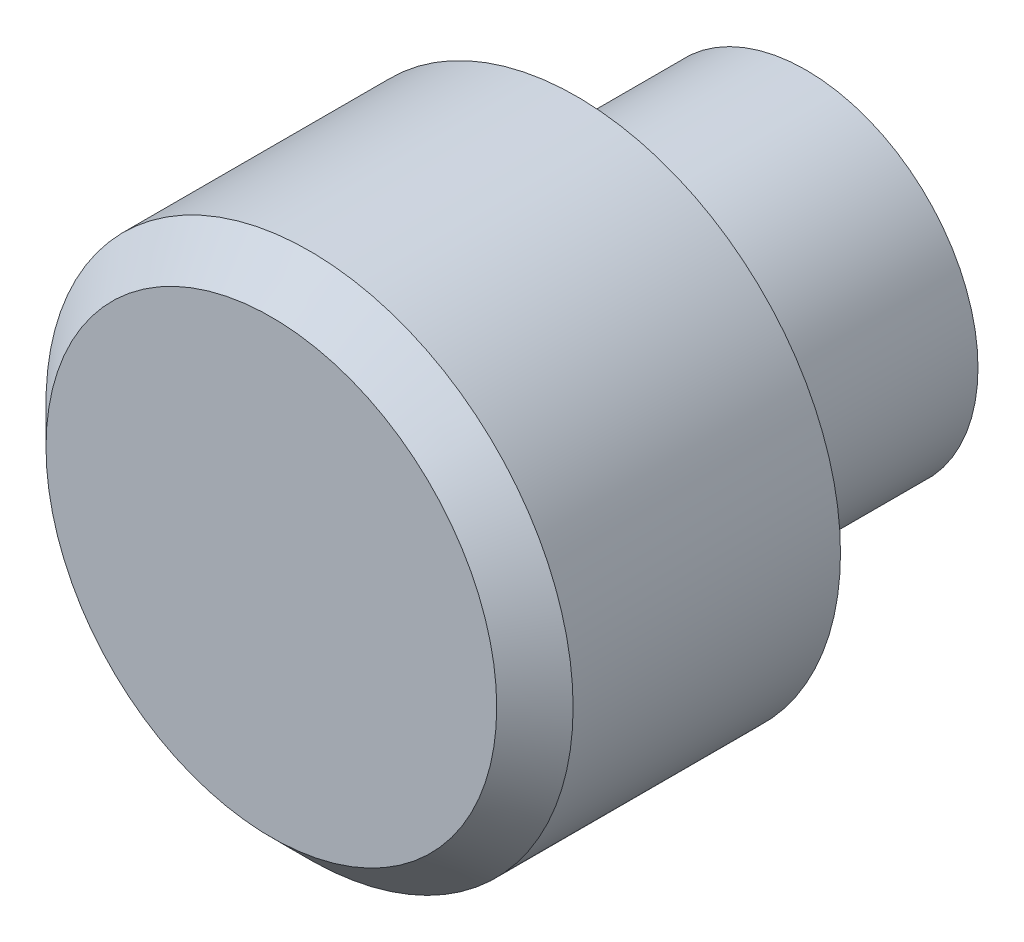
SolidWorks part; units mm, degrees
ref_plane "Front Plane" through (0, 0, 0) normal (0, 0, 1) x (1, 0, 0)
ref_plane "Top Plane" through (0, 0, 0) normal (0, 1, 0) x (1, 0, 0)
ref_plane "Right Plane" through (0, 0, 0) normal (1, 0, 0) x (0, 0, -1)
sketch "Sketch5" plane through (0, 0, 0) normal (0, 0, 1) x (1, 0, 0)
  circle A0 centre (0, 0) radius 11.25
  dimension "D1" = 22.5
extrude "Boss-Extrude5" add sketch "Sketch5" along normal blind 15
sketch "Sketch6" plane through (0, 0, 15) normal (0, 0, 1) x (1, 0, 0)
  circle A0 centre (0, 0) radius 17.25
  dimension "D1" = 34.5
extrude "Boss-Extrude6" add sketch "Sketch6" along normal blind 20
chamfer "Chamfer2" distance 2.5 angle 45 1 edges at (17.25, 0, 35)
